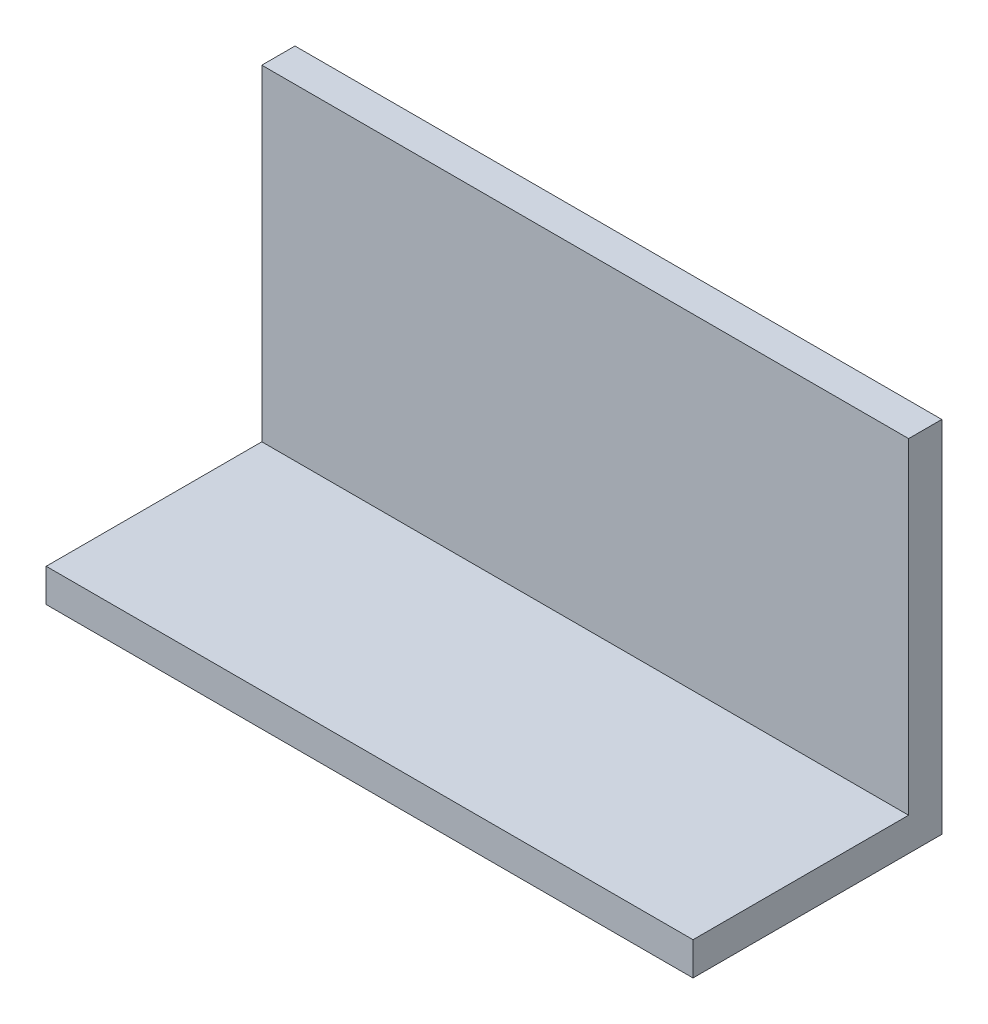
SolidWorks part; units mm, degrees
ref_plane "前视基准面" through (0, 0, 0) normal (0, 0, 1) x (1, 0, 0)
ref_plane "上视基准面" through (0, 0, 0) normal (0, 1, 0) x (1, 0, 0)
ref_plane "右视基准面" through (0, 0, 0) normal (1, 0, 0) x (0, 0, -1)
sketch "草图1" plane through (0, 0, 0) normal (0, 0, 1) x (1, 0, 0)
  line L1 (0, 0) -> (234, 0)
  line L2 (0, 0) -> (0, 130)
  line L3 (0, 130) -> (234, 130)
  line L4 (234, 0) -> (234, 130)
  dimension "D1" = 234
  dimension "D2" = 130
extrude "凸台-拉伸1" add sketch "草图1" along normal blind 90
sketch "草图2" plane through (0, 0, 0) normal (-1, 0, 0) x (0, 0, 1)
  line L0 (0, 130) -> (0, 0) construction
  line L1 (90, 130) -> (12, 130)
  line L2 (90, 130) -> (90, 12)
  line L3 (90, 12) -> (12, 12)
  line L4 (12, 130) -> (12, 12)
  line L5 (90, 0) -> (0, 0) construction
  dimension "D1" = 12
  dimension "D2" = 12
extrude "切除-拉伸1" cut sketch "草图2" against normal through all
